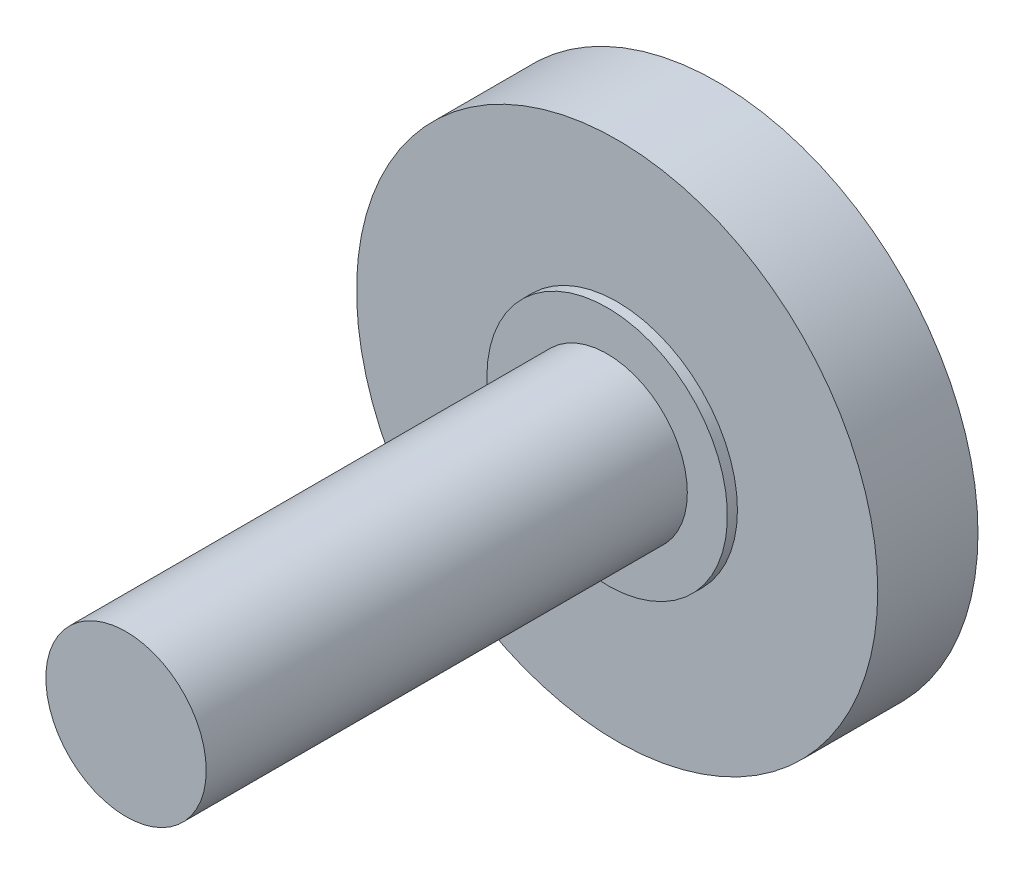
SolidWorks part; units mm, degrees
ref_plane "Front Plane" through (0, 0, 0) normal (0, 0, 1) x (1, 0, 0)
ref_plane "Top Plane" through (0, 0, 0) normal (0, 1, 0) x (1, 0, 0)
ref_plane "Right Plane" through (0, 0, 0) normal (1, 0, 0) x (0, 0, -1)
sketch "Sketch1" plane through (0, 0, 0) normal (0, 0, 1) x (1, 0, 0)
  circle A0 centre (0, 0) radius 13
extrude "Boss-Extrude1" add sketch "Sketch1" along normal blind 5
sketch "Sketch12" plane through (0, 0, 5) normal (0, 0, 1) x (1, 0, 0)
  circle A0 centre (0, 0) radius 4
extrude "Cut-Extrude6" cut sketch "Sketch12" against normal blind 5
sketch "Sketch13" plane through (0, 0, 0) normal (0, 0, -1) x (-1, 0, 0)
  circle A0 centre (0, 0) radius 6
extrude "Boss-Extrude7" add sketch "Sketch13" along normal blind 0.5
sketch "Sketch14" plane through (0, 0, -0.5) normal (0, 0, -1) x (-1, 0, 0)
  circle A0 centre (0, 0) radius 4
extrude "Cut-Extrude7" cut sketch "Sketch14" against normal blind 0.5
ref_plane "Plane1" through (0, 0, 2.5) normal (0, 0, -1) x (-1, 0, 0)
mirror "Mirror2" about plane through (0, 0, 2.5) normal (0, 0, -1) of "Boss-Extrude7", "Cut-Extrude7"
sketch "Sketch15" plane through (0, 0, -0.5) normal (0, 0, -1) x (-1, 0, 0)
  line L1 (5.7438, 4.094) -> (-0.6736, 7.0213)
  line L2 (-0.6736, 7.0213) -> (-6.4174, 2.9273)
  line L3 (-6.4174, 2.9273) -> (-5.7438, -4.094)
  line L4 (-5.7438, -4.094) -> (0.6736, -7.0213)
  line L5 (0.6736, -7.0213) -> (6.4174, -2.9273)
  line L6 (6.4174, -2.9273) -> (5.7438, 4.094)
  circle A0 centre (0, 0) radius 6.1085 construction
extrude "Boss-Extrude8" add sketch "Sketch15" along normal blind 3
sketch "Sketch16" plane through (0, 0, -0.5) normal (0, 0, 1) x (1, 0, 0)
  circle A0 centre (0, 0) radius 4
extrude "Boss-Extrude9" add sketch "Sketch16" along normal blind 30
sketch "Sketch18" plane through (0, 0, 29.5) normal (0, 0, 1) x (1, 0, 0)
  circle A0 centre (0, 0) radius 4
